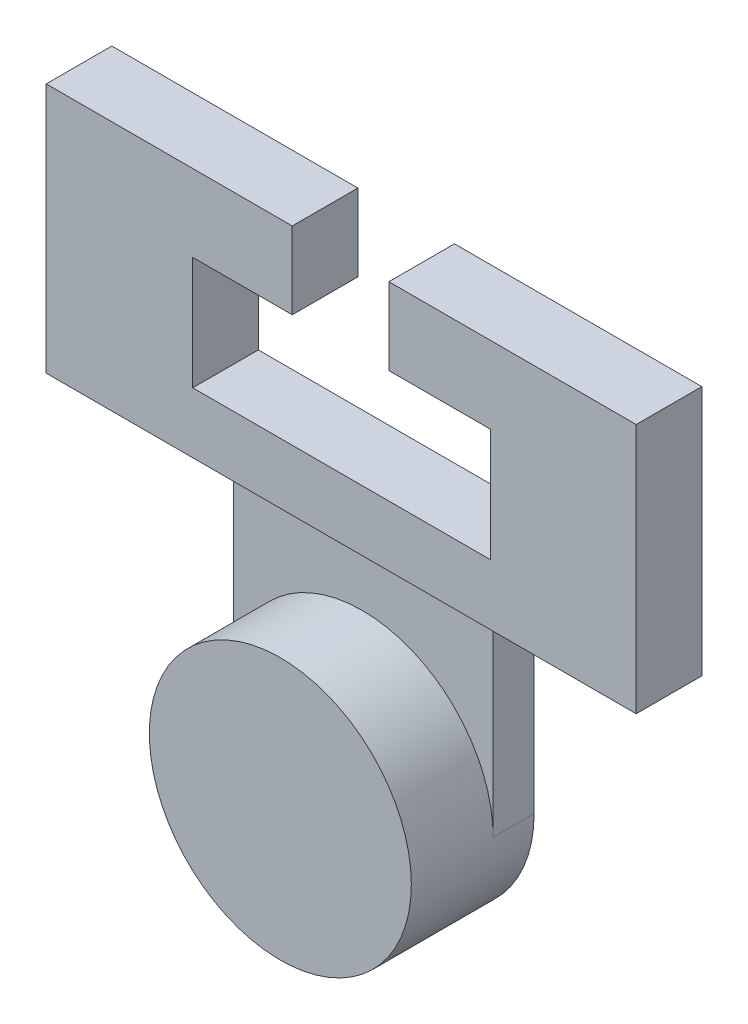
SolidWorks part; units mm, degrees
material "6061 Alloy"
ref_plane "Front Plane" through (0, 0, 0) normal (0, 0, 1) x (1, 0, 0)
ref_plane "Top Plane" through (0, 0, 0) normal (0, 1, 0) x (1, 0, 0)
ref_plane "Right Plane" through (0, 0, 0) normal (1, 0, 0) x (0, 0, -1)
sketch "Sketch1" plane through (0, 0, 0) normal (0, 0, 1) x (1, 0, 0)
  circle A0 centre (0, 0) radius 10.16
  dimension "D1" = 20.32
extrude "Boss-Extrude1" add sketch "Sketch1" against normal blind 9.525
sketch "Sketch2" plane through (0, 0, -9.525) normal (0, 0, -1) x (-1, 0, 0)
  line L1 (-10.16, 0) -> (9.9915, 0)
  line L2 (-10.16, 0) -> (-10.16, 15.7545)
  line L3 (-10.16, 15.7545) -> (9.9915, 15.7545)
  line L4 (9.9915, 0) -> (9.9915, 15.7545)
  circle A0 centre (0, 0) radius 10.16 construction
extrude "Boss-Extrude4" add sketch "Sketch2" against normal blind 3.175
sketch "Sketch3" plane through (0, 15.7545, 0) normal (0, 1, 0) x (1, 0, 0)
  line L0 (-9.9915, 9.525) -> (-22.594, 9.525)
  line L1 (-22.594, 9.525) -> (-22.594, 4.4351)
  line L2 (-22.594, 4.4351) -> (23.1661, 4.4351)
  line L3 (23.1661, 4.4351) -> (23.1661, 9.525)
  line L4 (23.1661, 9.525) -> (-9.9915, 9.525)
extrude "Boss-Extrude5" add sketch "Sketch3" along normal blind 4.699
sketch "Sketch4" plane through (0, 20.4535, 0) normal (0, 1, 0) x (1, 0, 0)
  line L0 (-22.594, 4.4351) -> (23.1661, 4.4351) construction
  line L1 (-22.594, 9.525) -> (-11.2293, 9.525)
  line L2 (-22.594, 9.525) -> (-22.594, 4.4351)
  line L3 (-22.594, 4.4351) -> (-11.2293, 4.4351)
  line L4 (-11.2293, 9.525) -> (-11.2293, 4.4351)
  line L5 (23.1661, 9.525) -> (-22.594, 9.525) construction
  line L6 (23.1661, 9.525) -> (11.852, 9.525)
  line L7 (23.1661, 9.525) -> (23.1661, 4.4351)
  line L8 (23.1661, 4.4351) -> (11.852, 4.4351)
  line L9 (11.852, 9.525) -> (11.852, 4.4351)
extrude "Boss-Extrude6" add sketch "Sketch4" along normal blind 8.763
sketch "Sketch5" plane through (0, 29.2165, 0) normal (0, 1, 0) x (1, 0, 0)
  line L0 (-11.2293, 4.4351) -> (11.852, 4.4351) construction
  line L1 (-22.594, 9.525) -> (-3.5102, 9.525)
  line L2 (-22.594, 9.525) -> (-22.594, 4.4351)
  line L3 (-22.594, 4.4351) -> (-3.5102, 4.4351)
  line L4 (-3.5102, 9.525) -> (-3.5102, 4.4351)
  line L6 (23.1661, 9.525) -> (3.9811, 9.525)
  line L7 (23.1661, 9.525) -> (23.1661, 4.4351)
  line L8 (23.1661, 4.4351) -> (3.9811, 4.4351)
  line L9 (3.9811, 9.525) -> (3.9811, 4.4351)
extrude "Boss-Extrude7" add sketch "Sketch5" along normal blind 5.969
